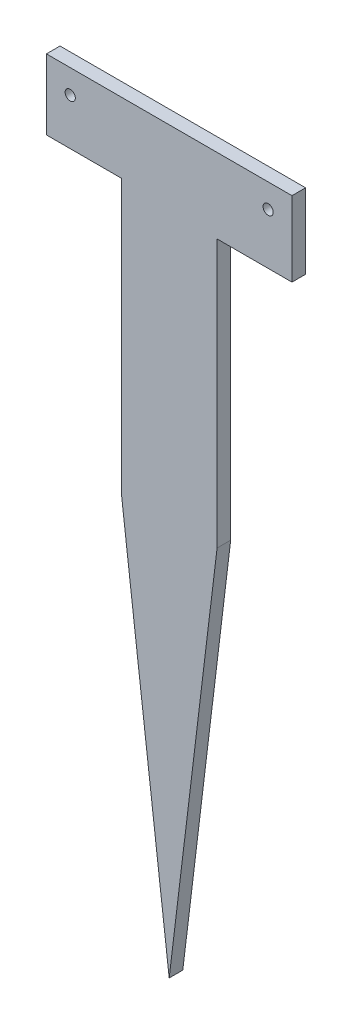
SolidWorks part; units mm, degrees
ref_plane "前视基准面" through (0, 0, 0) normal (0, 0, 1) x (1, 0, 0)
ref_plane "上视基准面" through (0, 0, 0) normal (0, 1, 0) x (1, 0, 0)
ref_plane "右视基准面" through (0, 0, 0) normal (1, 0, 0) x (0, 0, -1)
sketch "草图1" plane through (0, 0, 0) normal (0, 0, 1) x (1, 0, 0)
  line L0 (0, 0) -> (58.12, 0) construction
  line L9 (-7, 7) -> (65.12, 7)
  line L10 (65.12, 7) -> (65.12, -15)
  line L11 (65.12, -15) -> (43.12, -15)
  line L12 (43.12, -15) -> (43.12, -93.6178)
  line L13 (43.12, -93.6178) -> (15, -93.6178) construction
  line L14 (15, -93.6178) -> (15, -13.6178)
  line L15 (15, -13.6178) -> (-7, -13.6178)
  line L16 (-7, -13.6178) -> (-7, 7)
  line L17 (15, -93.6178) -> (29.06, -210)
  line L18 (29.06, -210) -> (43.12, -93.6178)
  circle A0 centre (0, 0) radius 1.5
  circle A1 centre (58.12, 0) radius 1.5
  dimension "D1" = 7
  dimension "D5" = 22
  dimension "D2" = 58.12
  dimension "D3" = 7
  dimension "D4" = 22
  dimension "D6" = 7
  dimension "D7" = 80
  dimension "D8" = 210
extrude "凸台-拉伸1" add sketch "草图1" along normal blind 4
